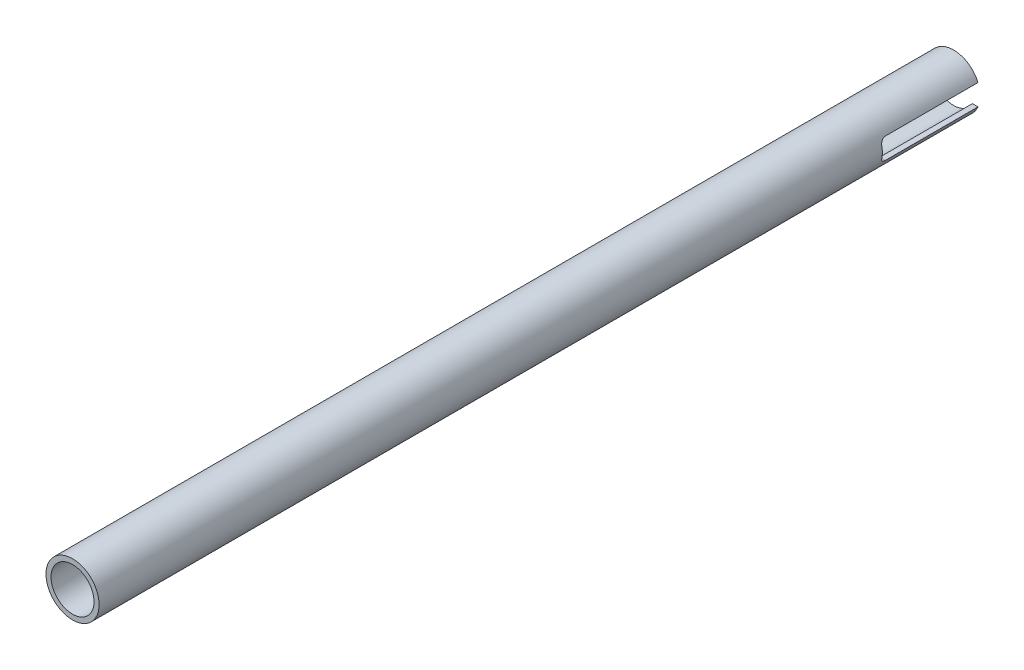
SolidWorks part; units mm, degrees
material "AISI 4130 Steel, annealed at 865C"
ref_plane "Front Plane" through (0, 0, 0) normal (0, 0, 1) x (1, 0, 0)
ref_plane "Top Plane" through (0, 0, 0) normal (0, 1, 0) x (1, 0, 0)
ref_plane "Right Plane" through (0, 0, 0) normal (1, 0, 0) x (0, 0, -1)
sketch "Sketch1" plane through (0, 0, 0) normal (0, 0, 1) x (1, 0, 0)
  circle A0 centre (0, 0) radius 6.477
  circle A1 centre (0, 0) radius 8.001
  dimension "D1" = 12.954
  dimension "D2" = 16.002
extrude "Boss-Extrude1" add sketch "Sketch1" along normal blind 265.43
sketch "Sketch2" plane through (0, 0, 0) normal (1, 0, 0) x (0, 0, -1)
  line L0 (0, 3.175) -> (-27.94, 3.175)
  line L1 (0, 55) -> (0, -55) construction
  line L2 (-27.94, -3.175) -> (0, -3.175)
  line L3 (-29.464, 1.651) -> (-29.464, -1.651)
  line L4 (0, -8.001) -> (0, 8.001) construction
  arc A0 (-29.464, 1.651) -> (-27.94, 3.175) centre (-27.94, 1.651) cw
  arc A1 (-27.94, -3.175) -> (-29.464, -1.651) centre (-27.94, -1.651) cw
  dimension "D5" = 27.94
  dimension "D6" = 29.464
  dimension "D1" = 29.464
  dimension "D2" = 27.94
  dimension "D3" = 6.35
  dimension "D4" = 3.175
extrude "Cut-Extrude1" cut sketch "Sketch2" against normal through all both and the other way through all
